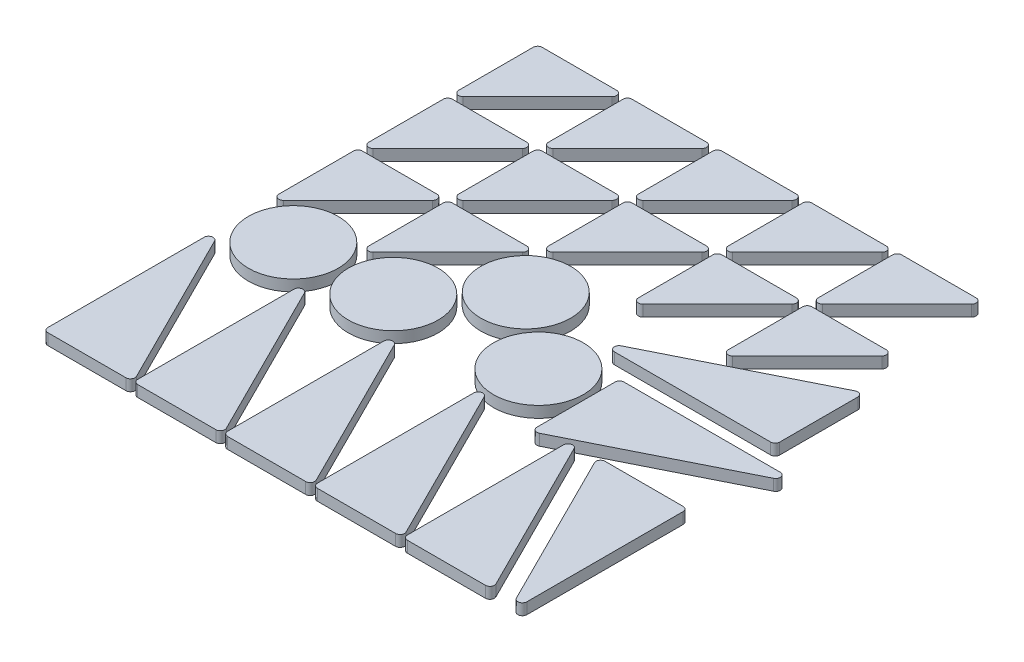
SolidWorks part; units mm, degrees
ref_plane "Front Plane" through (0, 0, 0) normal (0, 0, 1) x (1, 0, 0)
ref_plane "Top Plane" through (0, 0, 0) normal (0, 1, 0) x (1, 0, 0)
ref_plane "Right Plane" through (0, 0, 0) normal (1, 0, 0) x (0, 0, -1)
sketch "Sketch1" plane through (0, 0, 0) normal (0, 1, 0) x (1, 0, 0)
  line L6 (0, 0) -> (0, 304.8)
  line L7 (0, 0) -> (304.8, 0)
  line L8 (0, 304.8) -> (304.8, 304.8)
  line L9 (304.8, 0) -> (304.8, 304.8)
  dimension "D1" = 304.8
  dimension "D2" = 304.8
extrude "Boss-Extrude1" add sketch "Sketch1" along normal blind 6.35
sketch "Sketch2" plane through (0, 6.35, 0) normal (0, 1, 0) x (1, 0, 0)
  line L0 (12.7, 289.56) -> (12.7, 247.4321)
  line L1 (15.24, 292.1) -> (57.3679, 292.1)
  line L2 (17.0361, 245.6361) -> (59.1639, 287.7639)
  line L3 (304.8, 304.8) -> (0, 304.8) construction
  line L4 (0, 304.8) -> (0, 0) construction
  line L5 (67.8361, 245.6361) -> (109.9639, 287.7639)
  line L6 (66.04, 292.1) -> (108.1679, 292.1)
  line L7 (63.5, 289.56) -> (63.5, 247.4321)
  line L8 (118.6361, 245.6361) -> (160.7639, 287.7639)
  line L9 (116.84, 292.1) -> (158.9679, 292.1)
  line L10 (114.3, 289.56) -> (114.3, 247.4321)
  line L11 (169.4361, 245.6361) -> (211.5639, 287.7639)
  line L12 (167.64, 292.1) -> (209.7679, 292.1)
  line L13 (165.1, 289.56) -> (165.1, 247.4321)
  line L14 (220.2361, 245.6361) -> (262.3639, 287.7639)
  line L15 (218.44, 292.1) -> (260.5679, 292.1)
  line L16 (215.9, 289.56) -> (215.9, 247.4321)
  line L17 (67.8361, 194.8361) -> (109.9639, 236.9639)
  line L18 (66.04, 241.3) -> (108.1679, 241.3)
  line L19 (63.5, 238.76) -> (63.5, 196.6321)
  line L20 (118.6361, 194.8361) -> (160.7639, 236.9639)
  line L21 (116.84, 241.3) -> (158.9679, 241.3)
  line L22 (114.3, 238.76) -> (114.3, 196.6321)
  line L23 (169.4361, 194.8361) -> (211.5639, 236.9639)
  line L24 (167.64, 241.3) -> (209.7679, 241.3)
  line L25 (165.1, 238.76) -> (165.1, 196.6321)
  line L26 (220.2361, 194.8361) -> (262.3639, 236.9639)
  line L27 (218.44, 241.3) -> (260.5679, 241.3)
  line L28 (215.9, 238.76) -> (215.9, 196.6321)
  line L29 (17.0361, 194.8361) -> (59.1639, 236.9639)
  line L30 (15.24, 241.3) -> (57.3679, 241.3)
  line L31 (12.7, 238.76) -> (12.7, 196.6321)
  line L32 (17.0361, 144.0361) -> (59.1639, 186.1639)
  line L33 (15.24, 190.5) -> (57.3679, 190.5)
  line L34 (12.7, 187.96) -> (12.7, 145.8321)
  line L35 (67.8361, 144.0361) -> (109.9639, 186.1639)
  line L36 (66.04, 190.5) -> (108.1679, 190.5)
  line L37 (63.5, 187.96) -> (63.5, 145.8321)
  line L38 (12.7, 15.24) -> (12.7, 103.5404)
  line L39 (15.24, 12.7) -> (59.3902, 12.7)
  line L40 (0, 0) -> (304.8, 0) construction
  line L41 (17.5118, 104.6763) -> (61.662, 16.3759)
  line L42 (68.3118, 104.6763) -> (112.462, 16.3759)
  line L43 (66.04, 12.7) -> (110.1902, 12.7)
  line L44 (63.5, 15.24) -> (63.5, 103.5404)
  line L45 (119.1118, 104.6763) -> (163.262, 16.3759)
  line L46 (116.84, 12.7) -> (160.9902, 12.7)
  line L47 (114.3, 15.24) -> (114.3, 103.5404)
  line L48 (169.9118, 104.6763) -> (214.062, 16.3759)
  line L49 (167.64, 12.7) -> (211.7902, 12.7)
  line L50 (165.1, 15.24) -> (165.1, 103.5404)
  line L51 (220.7118, 104.6763) -> (264.862, 16.3759)
  line L52 (218.44, 12.7) -> (262.5902, 12.7)
  line L53 (215.9, 15.24) -> (215.9, 103.5404)
  line L54 (277.5522, 15.24) -> (233.402, 103.5404)
  line L55 (279.824, 107.2163) -> (235.6738, 107.2163)
  line L56 (282.364, 104.6763) -> (282.364, 16.3759)
  line L57 (291.6937, 146.5547) -> (203.3933, 102.4045)
  line L58 (199.7174, 148.8265) -> (199.7174, 104.6763)
  line L59 (202.2574, 151.3665) -> (290.5578, 151.3665)
  line L60 (183.6711, 168.254) -> (271.9715, 212.4042)
  line L61 (275.6474, 165.9822) -> (275.6474, 210.1324)
  line L62 (273.1074, 163.4422) -> (184.8071, 163.4422)
  arc A0 (59.1639, 287.7639) -> (57.3679, 292.1) centre (57.3679, 289.56) ccw
  arc A1 (12.7, 289.56) -> (15.24, 292.1) centre (15.24, 289.56) cw
  arc A2 (17.0361, 245.6361) -> (12.7, 247.4321) centre (15.24, 247.4321) cw
  arc A3 (67.8361, 245.6361) -> (63.5, 247.4321) centre (66.04, 247.4321) cw
  arc A4 (109.9639, 287.7639) -> (108.1679, 292.1) centre (108.1679, 289.56) ccw
  arc A5 (63.5, 289.56) -> (66.04, 292.1) centre (66.04, 289.56) cw
  arc A6 (118.6361, 245.6361) -> (114.3, 247.4321) centre (116.84, 247.4321) cw
  arc A7 (160.7639, 287.7639) -> (158.9679, 292.1) centre (158.9679, 289.56) ccw
  arc A8 (114.3, 289.56) -> (116.84, 292.1) centre (116.84, 289.56) cw
  arc A9 (169.4361, 245.6361) -> (165.1, 247.4321) centre (167.64, 247.4321) cw
  arc A10 (211.5639, 287.7639) -> (209.7679, 292.1) centre (209.7679, 289.56) ccw
  arc A11 (165.1, 289.56) -> (167.64, 292.1) centre (167.64, 289.56) cw
  arc A12 (220.2361, 245.6361) -> (215.9, 247.4321) centre (218.44, 247.4321) cw
  arc A13 (262.3639, 287.7639) -> (260.5679, 292.1) centre (260.5679, 289.56) ccw
  arc A14 (215.9, 289.56) -> (218.44, 292.1) centre (218.44, 289.56) cw
  arc A15 (67.8361, 194.8361) -> (63.5, 196.6321) centre (66.04, 196.6321) cw
  arc A16 (109.9639, 236.9639) -> (108.1679, 241.3) centre (108.1679, 238.76) ccw
  arc A17 (63.5, 238.76) -> (66.04, 241.3) centre (66.04, 238.76) cw
  arc A18 (118.6361, 194.8361) -> (114.3, 196.6321) centre (116.84, 196.6321) cw
  arc A19 (160.7639, 236.9639) -> (158.9679, 241.3) centre (158.9679, 238.76) ccw
  arc A20 (114.3, 238.76) -> (116.84, 241.3) centre (116.84, 238.76) cw
  arc A21 (169.4361, 194.8361) -> (165.1, 196.6321) centre (167.64, 196.6321) cw
  arc A22 (211.5639, 236.9639) -> (209.7679, 241.3) centre (209.7679, 238.76) ccw
  arc A23 (165.1, 238.76) -> (167.64, 241.3) centre (167.64, 238.76) cw
  arc A24 (220.2361, 194.8361) -> (215.9, 196.6321) centre (218.44, 196.6321) cw
  arc A25 (262.3639, 236.9639) -> (260.5679, 241.3) centre (260.5679, 238.76) ccw
  arc A26 (215.9, 238.76) -> (218.44, 241.3) centre (218.44, 238.76) cw
  arc A27 (17.0361, 194.8361) -> (12.7, 196.6321) centre (15.24, 196.6321) cw
  arc A28 (59.1639, 236.9639) -> (57.3679, 241.3) centre (57.3679, 238.76) ccw
  arc A29 (12.7, 238.76) -> (15.24, 241.3) centre (15.24, 238.76) cw
  arc A30 (59.1639, 186.1639) -> (57.3679, 190.5) centre (57.3679, 187.96) ccw
  arc A31 (12.7, 187.96) -> (15.24, 190.5) centre (15.24, 187.96) cw
  arc A32 (17.0361, 144.0361) -> (12.7, 145.8321) centre (15.24, 145.8321) cw
  arc A33 (109.9639, 186.1639) -> (108.1679, 190.5) centre (108.1679, 187.96) ccw
  arc A34 (63.5, 187.96) -> (66.04, 190.5) centre (66.04, 187.96) cw
  arc A35 (67.8361, 144.0361) -> (63.5, 145.8321) centre (66.04, 145.8321) cw
  arc A36 (59.3902, 12.7) -> (61.662, 16.3759) centre (59.3902, 15.24) ccw
  arc A37 (15.24, 12.7) -> (12.7, 15.24) centre (15.24, 15.24) cw
  arc A38 (17.5118, 104.6763) -> (12.7, 103.5404) centre (15.24, 103.5404) ccw
  arc A39 (68.3118, 104.6763) -> (63.5, 103.5404) centre (66.04, 103.5404) ccw
  arc A40 (110.1902, 12.7) -> (112.462, 16.3759) centre (110.1902, 15.24) ccw
  arc A41 (66.04, 12.7) -> (63.5, 15.24) centre (66.04, 15.24) cw
  arc A42 (119.1118, 104.6763) -> (114.3, 103.5404) centre (116.84, 103.5404) ccw
  arc A43 (160.9902, 12.7) -> (163.262, 16.3759) centre (160.9902, 15.24) ccw
  arc A44 (116.84, 12.7) -> (114.3, 15.24) centre (116.84, 15.24) cw
  arc A45 (169.9118, 104.6763) -> (165.1, 103.5404) centre (167.64, 103.5404) ccw
  arc A46 (211.7902, 12.7) -> (214.062, 16.3759) centre (211.7902, 15.24) ccw
  arc A47 (167.64, 12.7) -> (165.1, 15.24) centre (167.64, 15.24) cw
  arc A48 (220.7118, 104.6763) -> (215.9, 103.5404) centre (218.44, 103.5404) ccw
  arc A49 (262.5902, 12.7) -> (264.862, 16.3759) centre (262.5902, 15.24) ccw
  arc A50 (218.44, 12.7) -> (215.9, 15.24) centre (218.44, 15.24) cw
  arc A51 (277.5522, 15.24) -> (282.364, 16.3759) centre (279.824, 16.3759) ccw
  arc A52 (235.6738, 107.2163) -> (233.402, 103.5404) centre (235.6738, 104.6763) ccw
  arc A53 (279.824, 107.2163) -> (282.364, 104.6763) centre (279.824, 104.6763) cw
  circle A54 centre (40.3786, 126.2972) radius 25.4
  circle A58 centre (93.9645, 129.2119) radius 25.4
  circle A59 centre (130.5106, 167.5517) radius 25.4
  circle A60 centre (171.526, 133.6961) radius 25.4
  arc A61 (291.6937, 146.5547) -> (290.5578, 151.3665) centre (290.5578, 148.8265) ccw
  arc A62 (199.7174, 104.6763) -> (203.3933, 102.4045) centre (202.2574, 104.6763) ccw
  arc A63 (199.7174, 148.8265) -> (202.2574, 151.3665) centre (202.2574, 148.8265) cw
  arc A64 (183.6711, 168.254) -> (184.8071, 163.4422) centre (184.8071, 165.9822) ccw
  arc A65 (275.6474, 210.1324) -> (271.9715, 212.4042) centre (273.1074, 210.1324) ccw
  arc A66 (275.6474, 165.9822) -> (273.1074, 163.4422) centre (273.1074, 165.9822) cw
  point P7 (12.7, 268.4961)
  point P10 (63.5, 292.1)
  point P13 (12.7, 292.1)
  point P16 (12.7, 241.3)
  point P123 (63.5, 12.7)
  point P126 (12.7, 12.7)
  point P129 (12.7, 114.3)
  dimension "D5" = 2.54
  dimension "D13" = 2.54
  dimension "D1" = 50.8
  dimension "D2" = 50.8
  dimension "D3" = 12.7
  dimension "D4" = 12.7
  dimension "D9" = 12.7
  dimension "D10" = 101.6
  dimension "D11" = 12.7
  dimension "D12" = 50.8
  dimension "D6" = 5
  dimension "D7" = 2
  dimension "D8" = 2
  dimension "D14" = 5
extrude "Cut-Extrude2" cut sketch "Sketch2" against normal through all flip side to cut
